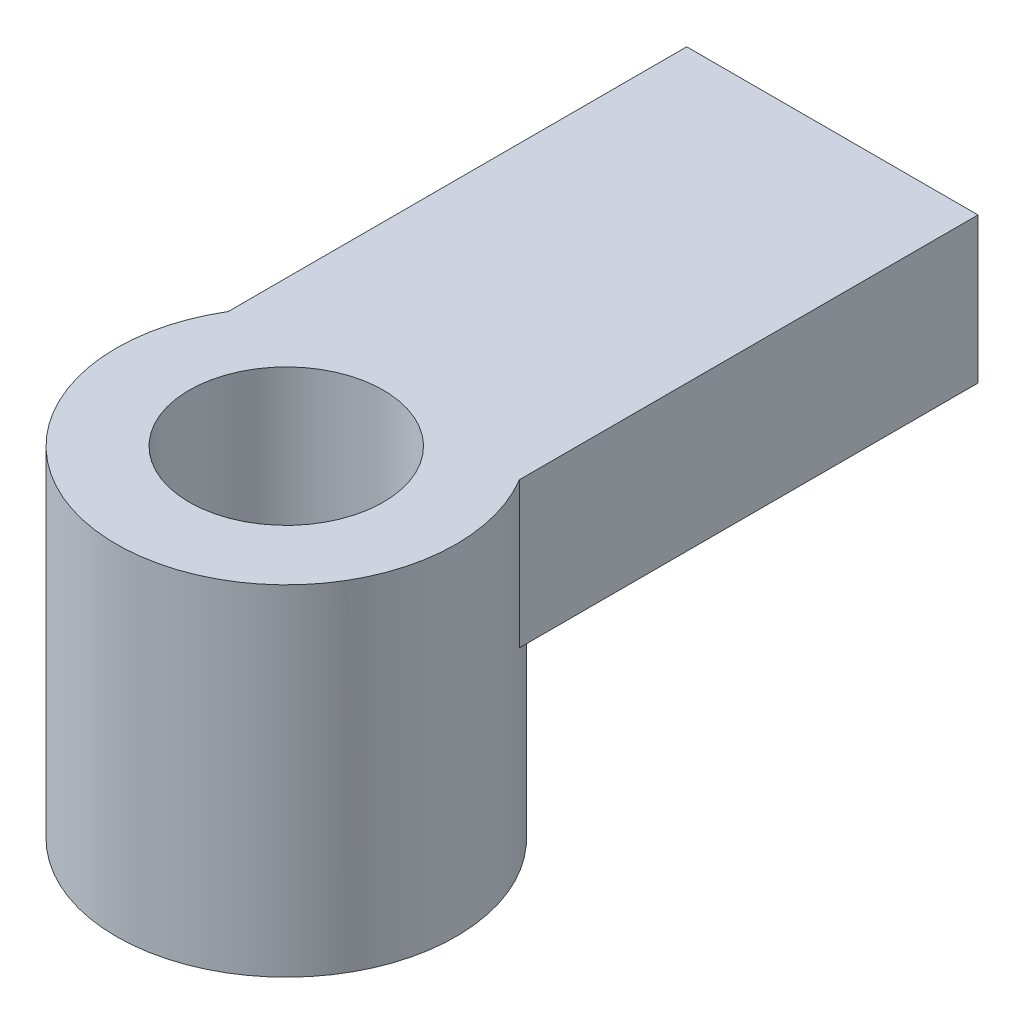
SolidWorks part; units mm, degrees
ref_plane "Front Plane" through (0, 0, 0) normal (0, 0, 1) x (1, 0, 0)
ref_plane "Top Plane" through (0, 0, 0) normal (0, 1, 0) x (1, 0, 0)
ref_plane "Right Plane" through (0, 0, 0) normal (1, 0, 0) x (0, 0, -1)
sketch "Sketch1" plane through (0, 0, 0) normal (0, 1, 0) x (1, 0, 0)
  circle A0 centre (0, 0) radius 16
  circle A1 centre (0, 0) radius 28
  dimension "D1" = 32
  dimension "D2" = 56
extrude "Boss-Extrude1" add sketch "Sketch1" along normal blind 56
sketch "Sketch3" plane through (0, 56, 0) normal (0, 1, 0) x (1, 0, 0)
  line L0 (0, 0) -> (0, 52.452) construction
  line L1 (-24, 90) -> (24, 90)
  line L2 (-24, 90) -> (-24, 14.4222)
  line L4 (24, 90) -> (24, 14.4222)
  circle A0 centre (0, 0) radius 28 construction
  arc A1 (24, 14.4222) -> (-24, 14.4222) centre (0, 0) ccw
  point P7 (0, 52.452)
  dimension "D1" = 90
  dimension "D2" = 48
extrude "Boss-Extrude2" add sketch "Sketch3" against normal blind 24
sketch "Sketch5" plane through (0, 0, -90) normal (0, 0, -1) x (-1, 0, 0)
  line L0 (-24, 32) -> (24, 32) construction
  circle A0 centre (0, 32) radius 16
  dimension "D1" = 32
extrude "Cut-Extrude2" cut sketch "Sketch5" against normal blind 40
